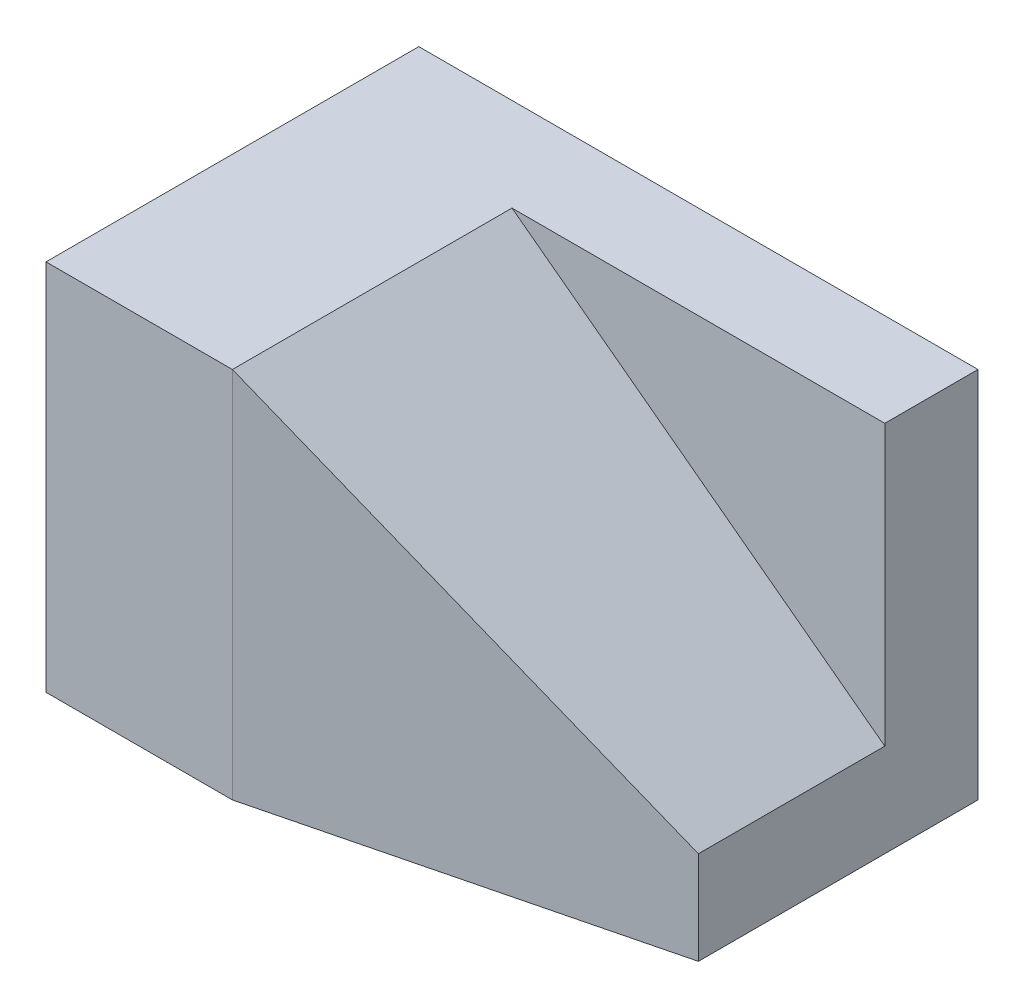
SolidWorks part; units mm, degrees
ref_plane "Front Plane" through (0, 0, 0) normal (0, 0, 1) x (1, 0, 0)
ref_plane "Top Plane" through (0, 0, 0) normal (0, 1, 0) x (1, 0, 0)
ref_plane "Right Plane" through (0, 0, 0) normal (1, 0, 0) x (0, 0, -1)
sketch "Sketch1" plane through (0, 0, 0) normal (0, 1, 0) x (1, 0, 0)
  line L0 (-29.6393, 22.6885) -> (-29.6393, -17.3115)
  line L1 (-29.6393, -17.3115) -> (-9.6393, -17.3115)
  line L2 (-9.6393, -17.3115) -> (-9.6393, 12.6885)
  line L3 (-9.6393, 12.6885) -> (30.3607, 12.6885)
  line L4 (30.3607, 12.6885) -> (30.3607, 22.6885)
  line L5 (30.3607, 22.6885) -> (-29.6393, 22.6885)
  dimension "D1" = 40
  dimension "D2" = 60
  dimension "D3" = 10
  dimension "D4" = 20
extrude "Boss-Extrude1" add sketch "Sketch1" along normal blind 40 contours L2 L3 L4 L5 L0 L1
sketch "Sketch2" plane through (-9.6393, 0, 0) normal (1, 0, 0) x (0, 0, -1)
  line L1 (-17.3115, 40) -> (12.6885, 40)
  line L2 (-17.3115, 40) -> (-17.3115, 0)
  line L3 (-17.3115, 0) -> (12.6885, 0)
  line L4 (12.6885, 40) -> (12.6885, 0)
sketch "Sketch3" plane through (30.3607, 0, 0) normal (1, 0, 0) x (0, 0, -1)
  line L0 (-17.3115, 40) -> (-17.3115, 0) construction
  line L1 (12.6885, 0) -> (-7.3115, 0)
  line L2 (12.6885, 0) -> (12.6885, 10)
  line L3 (12.6885, 10) -> (-7.3115, 10)
  line L4 (-7.3115, 0) -> (-7.3115, 10)
  dimension "D1" = 10
  dimension "D2" = 10
loft "Loft1" add profiles "Sketch3", "Sketch2"
